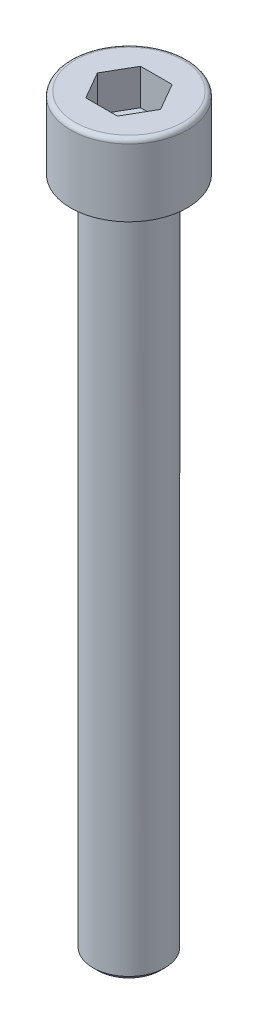
SolidWorks part; units mm, degrees
material "AISI 316 ｽﾃﾝﾚｽ鋼板 (SS)"
ref_plane "正面" through (0, 0, 0) normal (0, 0, 1) x (1, 0, 0)
ref_plane "平面" through (0, 0, 0) normal (0, 1, 0) x (1, 0, 0)
ref_plane "右側面" through (0, 0, 0) normal (1, 0, 0) x (0, 0, -1)
sketch "ｽｹｯﾁ1" plane through (0, 0, 0) normal (0, 1, 0) x (1, 0, 0)
  circle A0 centre (0, 0) radius 6.5
  dimension "D1" = 13
extrude "ﾎﾞｽ - 押し出し1" add sketch "ｽｹｯﾁ1" along normal blind 8
sketch "ｽｹｯﾁ2" plane through (0, 8, 0) normal (0, 1, 0) x (1, 0, 0)
  line L1 (3.5161, 0) -> (1.758, 3.045)
  line L2 (1.758, 3.045) -> (-1.758, 3.045)
  line L3 (-1.758, 3.045) -> (-3.5161, 0)
  line L4 (-3.5161, 0) -> (-1.758, -3.045)
  line L5 (-1.758, -3.045) -> (1.758, -3.045)
  line L6 (1.758, -3.045) -> (3.5161, 0)
  circle A0 centre (0, 0) radius 3.045 construction
  dimension "D1" = 3.045
extrude "ｶｯﾄ - 押し出し1" cut sketch "ｽｹｯﾁ2" against normal blind 4
fillet "ﾌｨﾚｯﾄ1" radius 0.5 1 edges at (0, 8, 6.5)
sketch "ｽｹｯﾁ3" plane through (0, 0, 0) normal (0, -1, 0) x (1, 0, 0)
  circle A0 centre (0, 0) radius 4
  dimension "D1" = 8
extrude "ﾎﾞｽ - 押し出し2" add sketch "ｽｹｯﾁ3" along normal blind 75
fillet "ﾌｨﾚｯﾄ2" radius 0.5 1 edges at (0, 0, 4)
chamfer "面取り1" distance 0.5 angle 45 1 edges at (0, -75, -4)
